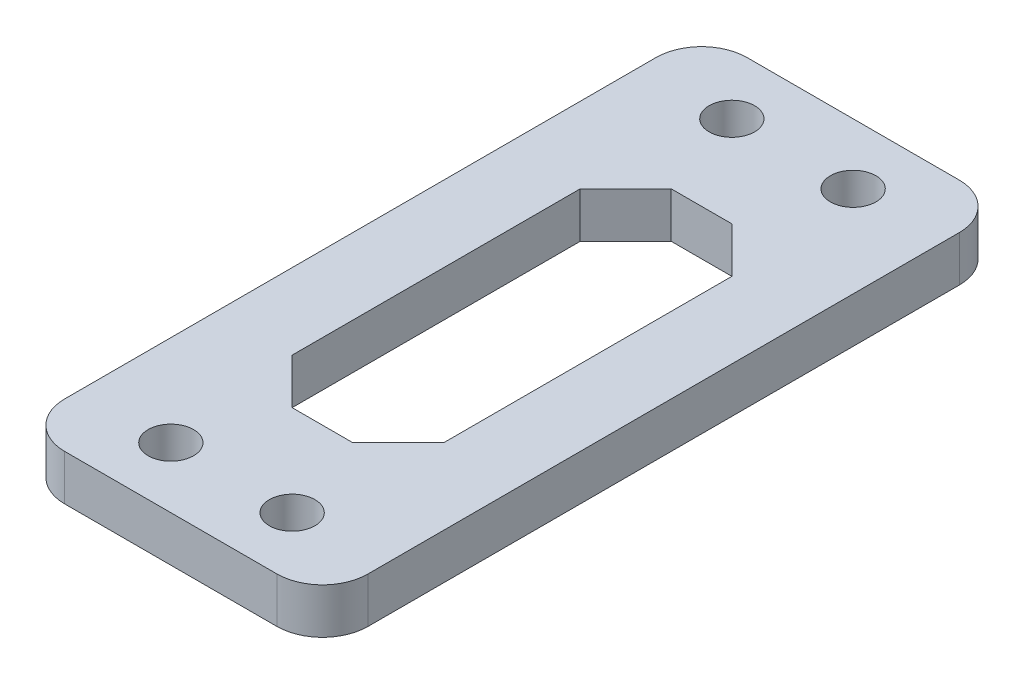
SolidWorks part; units mm, degrees
material "Thornel Mat VMA"
ref_plane "前视基准面" through (0, 0, 0) normal (0, 0, 1) x (1, 0, 0)
ref_plane "上视基准面" through (0, 0, 0) normal (0, 1, 0) x (1, 0, 0)
ref_plane "右视基准面" through (0, 0, 0) normal (1, 0, 0) x (0, 0, -1)
other "Configuration Table"
sketch "草图1" plane through (0, 0, 0) normal (0, 1, 0) x (1, 0, 0)
  line L0 (0, 0) -> (0, 41.7224) construction
  line L1 (-10, -22.5) -> (10, -22.5)
  line L2 (-10, -22.5) -> (-10, 22.5)
  line L3 (-10, 22.5) -> (10, 22.5)
  line L4 (10, -22.5) -> (10, 22.5)
  line L5 (-10, -22.5) -> (10, 22.5) construction
  line L6 (-10, 22.5) -> (10, -22.5) construction
  line L7 (0, 0) -> (20.4693, 0) construction
  line L9 (-5, -12.5) -> (5, -12.5)
  line L10 (-5, -12.5) -> (-5, 12.5)
  line L11 (-5, 12.5) -> (5, 12.5)
  line L12 (5, -12.5) -> (5, 12.5)
  line L13 (-5, -12.5) -> (5, 12.5) construction
  line L14 (-5, 12.5) -> (5, -12.5) construction
  circle A0 centre (-4, 18.5) radius 1.5
  circle A1 centre (4, 18.5) radius 1.5
  circle A2 centre (4, -18.5) radius 1.5
  circle A3 centre (-4, -18.5) radius 1.5
  point P0 (0, 0)
  dimension "D3" = 3
  dimension "D4" = 8
  dimension "D1" = 45
  dimension "D2" = 20
  dimension "D5" = 4
  dimension "D6" = 10
  dimension "D7" = 25
extrude "凸台-拉伸1" add sketch "草图1" along normal blind 3
chamfer "倒角1" distance 3 angle 45 4 edges at (5, 1.5, 12.5) (-5, 1.5, 12.5) (5, 1.5, -12.5) (-5, 1.5, -12.5)
fillet "圆角1" radius 3 4 edges at (-10, 1.5, 22.5) (10, 1.5, 22.5) (-10, 1.5, -22.5) (10, 1.5, -22.5)
